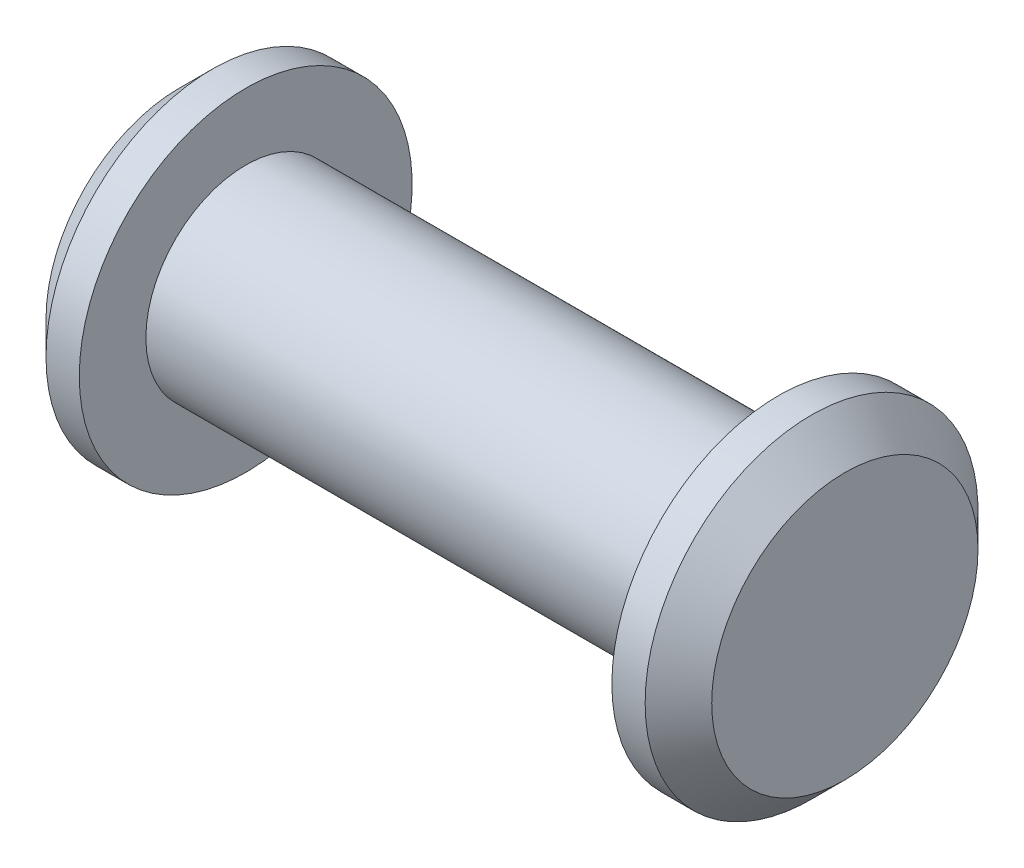
SolidWorks part; units mm, degrees
ref_plane "Front Plane" through (0, 0, 0) normal (0, 0, 1) x (1, 0, 0)
ref_plane "Top Plane" through (0, 0, 0) normal (0, 1, 0) x (1, 0, 0)
ref_plane "Right Plane" through (0, 0, 0) normal (1, 0, 0) x (0, 0, -1)
sketch "Sketch1" plane through (0, 0, 0) normal (0, 0, 1) x (1, 0, 0)
  line L0 (0, 0) -> (15829.9335, 0) construction
  line L1 (-20, 0) -> (-20, 8)
  line L2 (-20, 8) -> (-18, 10)
  line L3 (-18, 10) -> (-16, 10)
  line L4 (-16, 10) -> (-16, 6)
  line L5 (-16, 6) -> (16, 6)
  line L6 (16, 6) -> (16, 10)
  line L7 (16, 10) -> (18, 10)
  line L8 (20, 8) -> (20, 0)
  line L9 (18, 10) -> (20, 8)
  line L10 (0, 0) -> (0, 4.1583) construction
  line L11 (-20, 0) -> (20, 0)
  point P4 (-20, 10)
  point P6 (0, 6)
  point P11 (20, 10)
  dimension "D1" = 32
  dimension "D2" = 4
  dimension "D3" = 20
  dimension "D4" = 12
  dimension "D5" = 2
  dimension "D6" = 45
  dimension "D7" = 2
  dimension "D8" = 45
revolve "Revolve1" add sketch "Sketch1" angle 360 about L0
